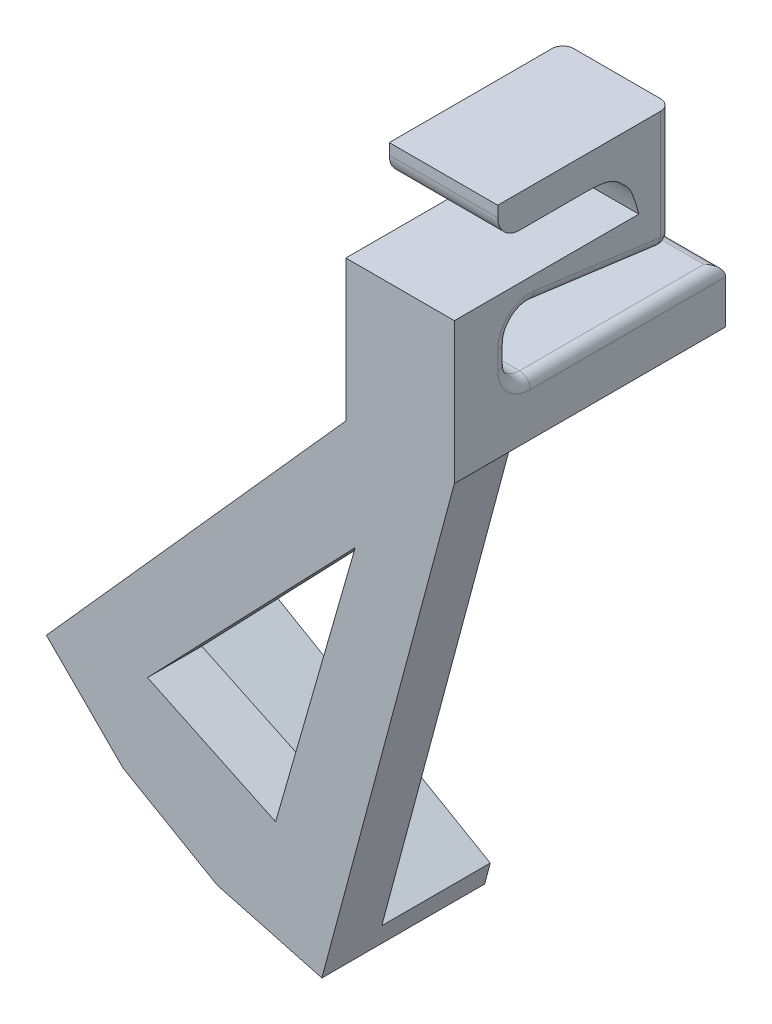
SolidWorks part; units mm, degrees
ref_plane "Front Plane" through (0, 0, 0) normal (0, 0, 1) x (1, 0, 0)
ref_plane "Top Plane" through (0, 0, 0) normal (0, 1, 0) x (1, 0, 0)
ref_plane "Right Plane" through (0, 0, 0) normal (1, 0, 0) x (0, 0, -1)
sketch "Sketch2" plane through (0, 0, 0) normal (1, 0, 0) x (0, 0, -1)
  line L0 (20, 13) -> (20, 20.213)
  line L1 (0, 0) -> (5, 0)
  line L2 (0, 0) -> (0, 13)
  line L3 (0, 13) -> (5, 13)
  line L4 (5, 0) -> (5, 13)
  line L6 (5, 0) -> (5, 3)
  line L9 (5, 13) -> (20, 13)
  line L10 (5, 13) -> (5, 11)
  line L11 (5, 11) -> (20, 11) construction
  line L12 (20, 13) -> (20, 11)
  line L13 (5, 5) -> (25, 5)
  line L14 (5, 5) -> (5, 0)
  line L15 (5, 0) -> (25, 0)
  line L16 (25, 5) -> (25, 0)
  line L17 (20, 20.213) -> (4, 20.213)
  line L18 (4, 20.213) -> (4, 19.213)
  line L19 (6, 17.213) -> (12.3497, 17.213)
  line L20 (17, 13) -> (20, 13)
  line L23 (20, 11) -> (20, 10.1422)
  line L24 (18.8678, 9.151) -> (5, 11)
  arc A0 (4, 19.213) -> (6, 17.213) centre (6, 19.213) ccw
  arc A1 (20, 10.1422) -> (18.8678, 9.151) centre (19, 10.1422) cw
  spline S0 degree 3 poles (12.3497, 17.213) (14.5346, 17.213) (15.6196, 15.8727) (16.3409, 15.5029) (17, 13) knots 0 0 0 0 0.495489 1 1 1 1
  point P24 (4, 17.213)
  point P25 (20, 9)
  dimension "D3" = 2
  dimension "D16" = 6.9797
  dimension "D12" = 1
  dimension "D1" = 13
  dimension "D2" = 3
  dimension "D4" = 3
  dimension "D5" = 4.213
  dimension "D6" = 6
  dimension "D7" = 2
  dimension "D8" = 5
  dimension "D9" = 15
  dimension "D10" = 20
  dimension "D11" = 2
  dimension "D14" = 2.9866
  dimension "D15" = 4.3328
extrude "Boss-Extrude1" add sketch "Sketch2" along normal blind 10
sketch "Sketch4" plane through (0, 0, 0) normal (0, 0, 1) x (1, 0, 0)
  line L0 (10, 0) -> (-2.2086, -45.5631)
  line L1 (-2.2086, -45.5631) -> (-11.8678, -42.9749)
  line L2 (-11.8678, -42.9749) -> (-20.5281, -37.9749)
  line L3 (-20.5281, -37.9749) -> (-27.5992, -30.9038)
  line L4 (-27.5992, -30.9038) -> (0, 0)
  line L6 (0, 0) -> (10, 0)
  line L7 (10, 0) -> (0, 0) construction
  line L8 (10, 5) -> (-3.4586, -45.2281) construction
  line L9 (10, 5) -> (0, 5) construction
  line L10 (10, 0) -> (10, 13) construction
  line L11 (-18.2774, -29.6218) -> (-6.4709, -35.2264)
  line L12 (-6.4709, -35.2264) -> (0.8649, -9.6768)
  line L13 (0.8649, -9.6768) -> (-18.2774, -29.6218)
  dimension "D1" = 15
  dimension "D2" = 165
  dimension "D3" = 165
  dimension "D4" = 10
  dimension "D5" = 52
extrude "Boss-Extrude2" add sketch "Sketch4" against normal up to surface (5 mm away) up to face at (5, 8, -5)
sketch "Sketch5" plane through (0, 0, -5) normal (0, 0, -1) x (-1, 0, 0)
  line L0 (2.2086, -45.5631) -> (11.8678, -42.9749)
  line L1 (11.8678, -42.9749) -> (20.5281, -37.9749)
  line L2 (20.5281, -37.9749) -> (27.5992, -30.9038)
  line L3 (27.5992, -30.9038) -> (26.267, -29.4121)
  line L4 (27.5992, -30.9038) -> (0, 0) construction
  line L5 (26.267, -29.4121) -> (1.691, -43.6312)
  line L6 (-10, 0) -> (2.2086, -45.5631) construction
  line L7 (1.691, -43.6312) -> (2.2086, -45.5631)
  dimension "D1" = 2
extrude "Boss-Extrude3" add sketch "Sketch5" along normal blind 10
fillet "Fillet1" radius 2 2 edges at (5, 5, -5) (5, 11, -5)
fillet "Fillet2" radius 1 15 edges at (0, 15.1776, -20) (0, 9.3898, -19.6587) (10, 15.1776, -20) (10, 9.3898, -19.6587) (0, 10.2204, -5.6826) (0, 7.8578, -5) (0, 5.5858, -5.5858) (0, 9.9245, -13.0661) (0, 5, -16) (5, 5, -25) (10, 5, -16) (10, 5.5858, -5.5858) (10, 7.8578, -5) (10, 10.2204, -5.6826) (10, 9.9245, -13.0661)
